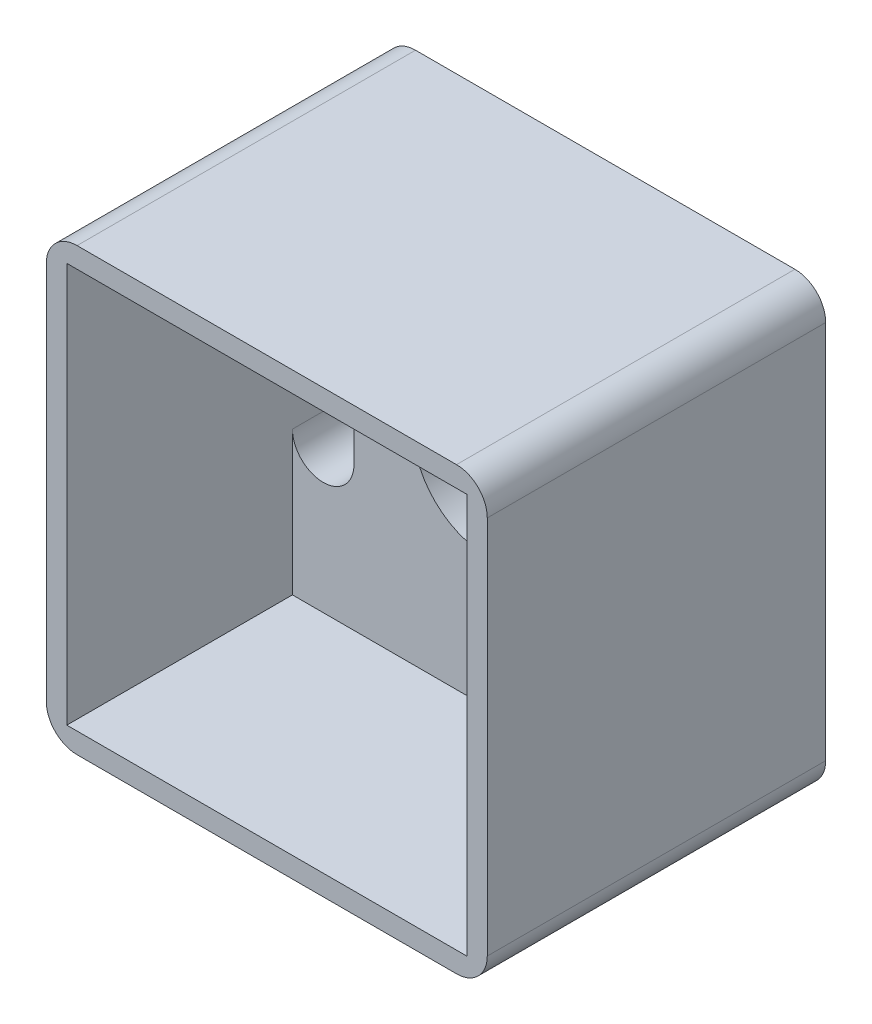
SolidWorks part; units mm, degrees
ref_plane "Front Plane" through (0, 0, 0) normal (1, 0, 0) x (0, 1, 0)
ref_plane "Top Plane" through (0, 0, 0) normal (0, 0, 1) x (0, 1, 0)
ref_plane "Right Plane" through (0, 0, 0) normal (0, 1, 0) x (-1, 0, 0)
sketch "Sketch1" plane through (0, 0, 0) normal (0, 0, 1) x (0, 1, 0)
  line L1 (0, 0) -> (-39, 0)
  line L2 (0, 0) -> (0, 39)
  line L3 (0, 39) -> (-39, 39)
  line L4 (-39, 0) -> (-39, 39)
  line L5 (-41, 41) -> (2, 41)
  line L6 (-41, 41) -> (-41, -2)
  line L7 (-41, -2) -> (2, -2)
  line L8 (2, 41) -> (2, -2)
  dimension "D1" = 39
  dimension "D2" = 39
  dimension "D3" = 2
  dimension "D4" = 2
  dimension "D5" = 2
  dimension "D6" = 2
  dimension "D7" = 43
extrude "Boss-Extrude1" add sketch "Sketch1" along normal blind 45 contours L6 L7 L8 L5
sketch "Sketch3" plane through (0, 0, 45) normal (0, 0, 1) x (1, 0, 0)
  line L0 (-3, -13) -> (-3, -25) construction
  line L1 (-39, 0) -> (0, 0)
  line L2 (-39, 0) -> (-39, -39.3012)
  line L3 (-39, -39.3012) -> (0, -39.3012)
  line L4 (0, 0) -> (0, -39.3012)
  line L5 (0, -13) -> (0, -25)
  line L6 (-6, -13) -> (-6, -25)
  line L7 (-36, -13) -> (-36, -25) construction
  line L8 (-33, -13) -> (-33, -25)
  line L9 (-39, -13) -> (-39, -25)
  circle A0 centre (-20, -19) radius 7.25
  arc A1 (0, -13) -> (-6, -13) centre (-3, -13) ccw
  arc A2 (-6, -25) -> (0, -25) centre (-3, -25) ccw
  arc A3 (-33, -13) -> (-39, -13) centre (-36, -13) ccw
  arc A4 (-39, -25) -> (-33, -25) centre (-36, -25) ccw
  circle A5 centre (-20, -3.5068) radius 3
  point P12 (-3, -19)
  point P20 (-36, -19)
  dimension "D7" = 14.5
  dimension "D8" = 12
  dimension "D14" = 6
  dimension "D16" = 3
  dimension "D17" = 3
  dimension "D9" = 12
  dimension "D1" = 2
  dimension "D2" = 1.6988
  dimension "D3" = 2
  dimension "D4" = 2
  dimension "D5" = 19
  dimension "D6" = 19
  dimension "D10" = 3
  dimension "D11" = 3
  dimension "D12" = 19
  dimension "D13" = 19
  dimension "D15" = 19
extrude "Cut-Extrude4" cut sketch "Sketch3" against normal blind 38 contours A5 | A0 | L6 A2 L5 A1 | L8 A4 L9 A3
sketch "Sketch6" plane through (0, 0, 45) normal (0, 0, 1) x (1, 0, 0)
  line L1 (-41, 2) -> (2, 2)
  line L2 (-41, 2) -> (-41, -41)
  line L3 (-41, -41) -> (2, -41)
  line L4 (2, 2) -> (2, -41)
  line L12 (-39, 0) -> (-39, -39)
  line L13 (-39, -39) -> (0, -39)
  line L14 (0, -39) -> (0, 0)
  line L15 (0, 0) -> (-39, 0)
  line L16 (-39, 0) -> (-39, -39)
  line L17 (-39, -39) -> (0, -39)
  line L18 (0, -39) -> (0, 0)
  line L19 (0, 0) -> (-39, 0)
  point P6 (0, 0)
  point P7 (0, 0)
  dimension "D1" = 2
extrude "Cut-Extrude5" cut sketch "Sketch6" against normal blind 22 contours L19 L16 L17 L18
sketch "Sketch7" plane through (0, 0, 0) normal (0, 0, -1) x (1, 0, 0)
  line L1 (-29.2126, 9.8159) -> (-10.8126, 9.8159)
  line L2 (-29.2126, 9.8159) -> (-29.2126, 28.2159)
  line L3 (-29.2126, 28.2159) -> (-10.8126, 28.2159)
  line L4 (-10.8126, 9.8159) -> (-10.8126, 28.2159)
  line L5 (-29.2126, 9.8159) -> (-10.8126, 28.2159) construction
  line L6 (-29.2126, 28.2159) -> (-10.8126, 9.8159) construction
  line L7 (-41, 41) -> (2, 41)
  line L8 (-41, 41) -> (-41, -2)
  line L9 (-41, -2) -> (2, -2)
  line L10 (2, 41) -> (2, -2)
  circle A0 centre (-20.0126, 19.0159) radius 7.0001
  point P12 (-41, 41)
  dimension "D1" = 18.4
  dimension "D2" = 18.4
extrude "Cut-Extrude8" cut sketch "Sketch7" against normal blind 12
fillet "Fillet2" radius 5 4 edges at (-29.2126, -28.2159, 6) (-29.2126, -9.8159, 6) (-10.8126, -9.8159, 6) (-10.8126, -28.2159, 6)
fillet "Fillet3" radius 3 4 edges at (2, 2, 28.5) (-41, 2, 28.5) (-41, -41, 28.5) (2, -41, 28.5)
sketch "Sketch10" plane through (0, 0, 0) normal (0, 0, -1) x (1, 0, 0)
  line L1 (-30.0162, 28.4596) -> (-9.7811, 28.4596)
  line L2 (-30.0162, 28.4596) -> (-30.0162, 9.1357)
  line L3 (-30.0162, 9.1357) -> (-9.7811, 9.1357)
  line L4 (-9.7811, 28.4596) -> (-9.7811, 9.1357)
extrude "Cut-Extrude9" cut sketch "Sketch10" against normal blind 7
